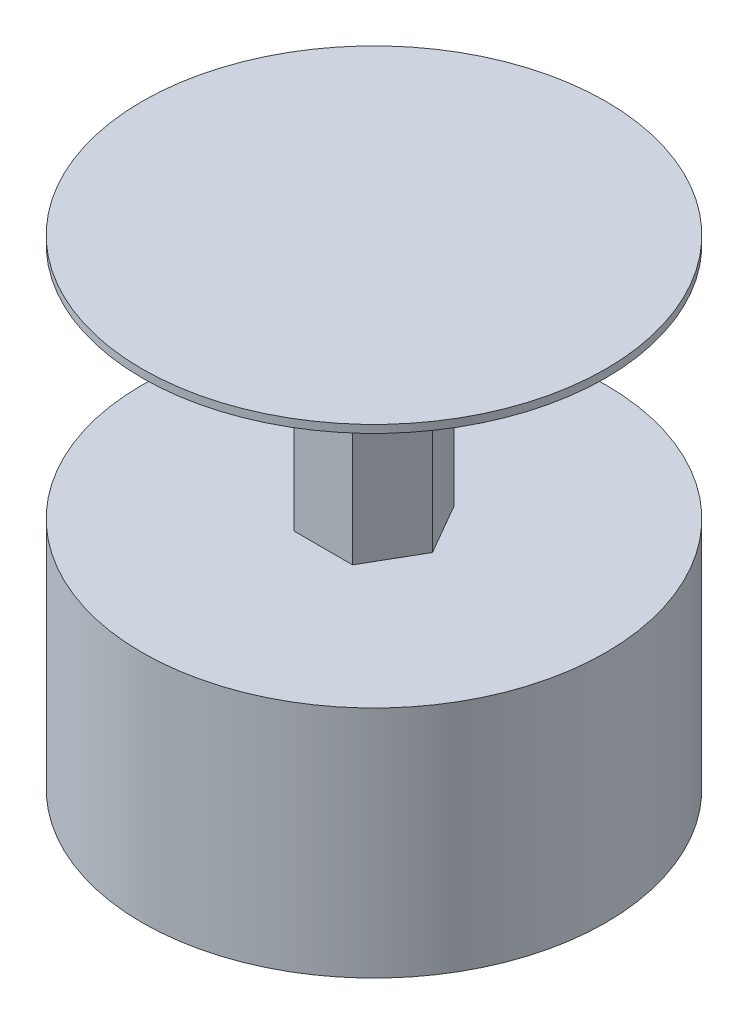
SolidWorks part; units mm, degrees
ref_plane "Front Plane" through (0, 0, 0) normal (0, 0, 1) x (1, 0, 0)
ref_plane "Top Plane" through (0, 0, 0) normal (0, 1, 0) x (1, 0, 0)
ref_plane "Right Plane" through (0, 0, 0) normal (1, 0, 0) x (0, 0, -1)
sketch "Sketch1" plane through (0, 0, 0) normal (0, 1, 0) x (1, 0, 0)
  line L0 (0, 0) -> (75, 0) construction
  line L1 (75, 0) -> (37.5, 64.9519) construction
  line L2 (37.5, 64.9519) -> (-37.5, 64.9519) construction
  line L3 (-37.5, 64.9519) -> (-75, 0) construction
  line L4 (-75, 0) -> (-37.5, -64.9519) construction
  line L5 (-37.5, -64.9519) -> (37.5, -64.9519) construction
  line L6 (37.5, -64.9519) -> (75, 0) construction
  line L7 (37.5, 64.9519) -> (75, 0) construction
  line L8 (37.5, 64.9519) -> (236.6858, 179.9519) construction
  line L9 (75, 0) -> (274.1858, 115) construction
  line L10 (236.6858, 179.9519) -> (274.1858, 115) construction
  circle A0 centre (0, 0) radius 64.9519 construction
  circle A1 centre (0, 0) radius 297.3262
  dimension "D1" = 75
  dimension "D2" = 230
extrude "Boss-Extrude1" add sketch "Sketch1" along normal blind 10
sketch "Sketch2" plane through (0, 0, 0) normal (0, -1, 0) x (1, 0, 0)
  line L0 (0, 0) -> (75, 0) construction
  line L1 (75, 0) -> (37.5, 64.9519)
  line L2 (37.5, 64.9519) -> (-37.5, 64.9519)
  line L3 (-37.5, 64.9519) -> (-75, 0)
  line L4 (-75, 0) -> (-37.5, -64.9519)
  line L5 (-37.5, -64.9519) -> (37.5, -64.9519)
  line L6 (37.5, -64.9519) -> (75, 0)
  circle A0 centre (0, 0) radius 64.9519 construction
  dimension "D1" = 75
extrude "Boss-Extrude2" add sketch "Sketch2" along normal blind 305
sketch "Sketch3" plane through (0, -305, 0) normal (0, -1, 0) x (1, 0, 0)
  circle A1 centre (0, 0) radius 297.3262
  circle A2 centre (0, 0) radius 297.3262
  dimension "D1" = 0
extrude "Boss-Extrude3" add sketch "Sketch3" along normal blind 300
sketch "Sketch5" plane through (0, -605, 0) normal (0, -1, 0) x (1, 0, 0)
  line L0 (327.0588, 0) -> (-327.0588, 0) construction
  line L1 (0, -327.0588) -> (0, 327.0588) construction
  circle A0 centre (150, 0) radius 5
  circle A1 centre (-150, 0) radius 5
  dimension "D1" = 10
  dimension "D2" = 150
extrude "Cut-Extrude1" cut sketch "Sketch5" against normal blind 10
sketch "Sketch6" plane through (0, -605, 0) normal (0, -1, 0) x (1, 0, 0)
  line L0 (0, -327.0588) -> (0, 327.0588) construction
  line L1 (327.0588, 0) -> (-327.0588, 0) construction
  circle A0 centre (0, 259.8262) radius 5
  circle A2 centre (0, 0) radius 297.3262 construction
  circle A3 centre (0, 0) radius 297.3262 construction
  circle A4 centre (0, -259.8262) radius 5
  point P9 (0, 297.3262)
  dimension "D1" = 10
  dimension "D2" = 37.5
extrude "Cut-Extrude2" cut sketch "Sketch6" against normal blind 10
